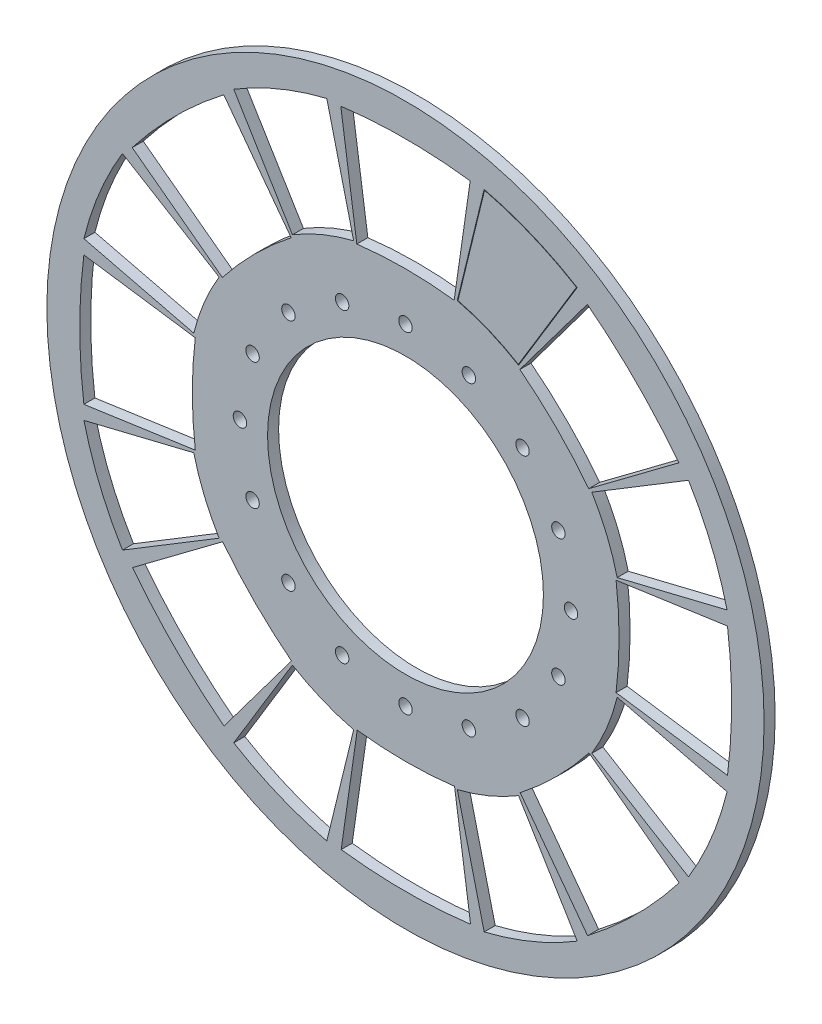
SolidWorks part; units mm, degrees
material "AISI 304"
ref_plane "Front Plane" through (0, 0, 0) normal (0, 0, 1) x (1, 0, 0)
ref_plane "Top Plane" through (0, 0, 0) normal (0, 1, 0) x (1, 0, 0)
ref_plane "Right Plane" through (0, 0, 0) normal (1, 0, 0) x (0, 0, -1)
sketch "Sketch1" plane through (0, 0, 0) normal (0, 0, 1) x (1, 0, 0)
  line L0 (0, 0) -> (0, 441.7053) construction
  line L3 (0, 0) -> (185.4371, 447.6848) construction
  line L4 (46.943, 191.8401) -> (71.3058, 291.4026)
  line L9 (226.8514, -146.4443) -> (147.5642, -85.5018) construction
  line L10 (85.3562, -147.7098) -> (146.2341, -227.0473) construction
  line L11 (56.8537, -258.9599) -> (43.882, -159.8025) construction
  line L12 (-44.0933, -159.8025) -> (-57.1463, -258.9498) construction
  line L13 (-146.4443, -226.8514) -> (-85.5018, -147.5642) construction
  line L14 (-147.7098, -85.3562) -> (-227.0473, -146.2341) construction
  line L18 (102.4577, 168.8451) -> (155.632, 256.4736)
  line L19 (191.8401, 46.943) -> (291.4026, 71.3058)
  line L20 (168.8451, 102.4577) -> (256.4736, 155.632)
  line L21 (168.8451, -102.4577) -> (256.4736, -155.632)
  line L22 (191.8401, -46.943) -> (291.4026, -71.3058)
  line L23 (46.943, -191.8401) -> (71.3058, -291.4026)
  line L24 (102.4577, -168.8451) -> (155.632, -256.4736)
  line L25 (-102.4577, -168.8451) -> (-155.632, -256.4736)
  line L26 (-46.943, -191.8401) -> (-71.3058, -291.4026)
  line L27 (-191.8401, -46.943) -> (-291.4026, -71.3058)
  line L28 (-168.8451, -102.4577) -> (-256.4736, -155.632)
  line L29 (-168.8451, 102.4577) -> (-256.4736, 155.632)
  line L30 (-191.8401, 46.943) -> (-291.4026, 71.3058)
  line L31 (-46.943, 191.8401) -> (-71.3058, 291.4026)
  line L32 (-102.4577, 168.8451) -> (-155.632, 256.4736)
  line L33 (0, 0) -> (-125, 0) construction
  line L34 (0, 125) -> (85.3562, 125) construction
  circle A1 centre (0, 0) radius 325
  circle A2 centre (0, 0) radius 125
  circle A5 centre (0, 0) radius 197.5 construction
  circle A6 centre (0, 0) radius 300 construction
  arc A11 (146.2341, -227.0473) -> (226.8514, -146.4443) centre (-136.1908, 136.0452) ccw construction
  arc A12 (85.3562, -147.7098) -> (147.5642, -85.5018) centre (-136.1908, 136.0452) ccw construction
  arc A13 (-57.1463, -258.9498) -> (56.8537, -258.9599) centre (-0.1056, 197.5) ccw construction
  arc A14 (-44.0933, -159.8025) -> (43.882, -159.8025) centre (-0.1056, 197.5) ccw construction
  arc A15 (-227.0473, -146.2341) -> (-146.4443, -226.8514) centre (136.0452, 136.1908) ccw construction
  arc A16 (-147.7098, -85.3562) -> (-85.5018, -147.5642) centre (136.0452, 136.1908) ccw construction
  arc A20 (46.943, 191.8401) -> (102.4577, 168.8451) centre (0, 0) cw
  arc A21 (71.3058, 291.4026) -> (155.632, 256.4736) centre (0, 0) cw
  arc A22 (256.4736, 155.632) -> (291.4026, 71.3058) centre (0, 0) cw
  arc A23 (168.8451, 102.4577) -> (191.8401, 46.943) centre (0, 0) cw
  arc A24 (291.4026, -71.3058) -> (256.4736, -155.632) centre (0, 0) cw
  arc A25 (191.8401, -46.943) -> (168.8451, -102.4577) centre (0, 0) cw
  arc A26 (155.632, -256.4736) -> (71.3058, -291.4026) centre (0, 0) cw
  arc A27 (102.4577, -168.8451) -> (46.943, -191.8401) centre (0, 0) cw
  arc A28 (-71.3058, -291.4026) -> (-155.632, -256.4736) centre (0, 0) cw
  arc A29 (-46.943, -191.8401) -> (-102.4577, -168.8451) centre (0, 0) cw
  arc A30 (-256.4736, -155.632) -> (-291.4026, -71.3058) centre (0, 0) cw
  arc A31 (-168.8451, -102.4577) -> (-191.8401, -46.943) centre (0, 0) cw
  arc A32 (-291.4026, 71.3058) -> (-256.4736, 155.632) centre (0, 0) cw
  arc A33 (-191.8401, 46.943) -> (-168.8451, 102.4577) centre (0, 0) cw
  arc A34 (-155.632, 256.4736) -> (-71.3058, 291.4026) centre (0, 0) cw
  arc A35 (-102.4577, 168.8451) -> (-46.943, 191.8401) centre (0, 0) cw
  circle A36 centre (0, 150) radius 6.1
  circle A37 centre (57.4025, 138.5819) radius 6.1
  circle A38 centre (106.066, 106.066) radius 6.1
  circle A39 centre (138.5819, 57.4025) radius 6.1
  circle A40 centre (150, 0) radius 6.1
  circle A41 centre (138.5819, -57.4025) radius 6.1
  circle A42 centre (106.066, -106.066) radius 6.1
  circle A43 centre (57.4025, -138.5819) radius 6.1
  circle A44 centre (0, -150) radius 6.1
  circle A45 centre (-57.4025, -138.5819) radius 6.1
  circle A46 centre (-106.066, -106.066) radius 6.1
  circle A47 centre (-138.5819, -57.4025) radius 6.1
  circle A48 centre (-150, 0) radius 6.1
  circle A49 centre (-138.5819, 57.4025) radius 6.1
  circle A50 centre (-106.066, 106.066) radius 6.1
  circle A51 centre (-57.4025, 138.5819) radius 6.1
  point P54 (0, 0)
  point P70 (0, 0)
  point P98 (0, 0)
  dimension "D1" = 250
  dimension "D2" = 650
  dimension "D5" = 395
  dimension "D3" = 600
  dimension "D6" = 17.5
  dimension "D7" = 8
  dimension "D8" = 12.2
  dimension "D4" = 22.5
  dimension "D9" = 150
  dimension "D10" = 16
extrude "Boss-Extrude1" add sketch "Sketch1" along normal blind 10
sketch "Sketch2" plane through (0, 0, 0) normal (0, 0, -1) x (-1, 0, 0)
  line L0 (-71.3058, 291.4026) -> (-46.943, 191.8401) construction
  line L1 (-102.4577, 168.8451) -> (-155.632, 256.4736) construction
  line L2 (-71.3058, 291.4026) -> (-46.943, 191.8401)
  line L3 (-102.4577, 168.8451) -> (-155.632, 256.4736)
  line L4 (-102.2893, 169.5314) -> (-154.9449, 256.3051)
  line L5 (-71.6725, 290.7977) -> (-47.5473, 192.2063)
  arc A0 (-46.943, 191.8401) -> (-102.4577, 168.8451) centre (0, 0) ccw construction
  arc A1 (-71.3058, 291.4026) -> (-155.632, 256.4736) centre (0, 0) ccw construction
  arc A2 (-46.943, 191.8401) -> (-102.4577, 168.8451) centre (0, 0) ccw
  arc A3 (-71.3058, 291.4026) -> (-155.632, 256.4736) centre (0, 0) ccw
  arc A4 (-47.5473, 192.2063) -> (-102.2893, 169.5314) centre (0, 0) ccw
  arc A5 (-71.6725, 290.7977) -> (-154.9449, 256.3051) centre (0, 0) ccw
  dimension "D1" = 0.5
extrude "Boss-Extrude2" add sketch "Sketch2" against normal blind 10 separate body contours A4 L4 A5 L5
sketch "Sketch3" plane through (0, 0, 0) normal (0, 0, -1) x (-1, 0, 0)
  line L0 (-57.5, 290.8396) -> (-43.25, 191.8401) construction
  line L1 (57.5, 290.8396) -> (43.25, 191.8401) construction
  line L2 (0, 194.4475) -> (0, 294.4475) construction
  line L3 (-46.943, 191.8401) -> (46.943, 191.8401) construction
  line L4 (71.3058, 291.4026) -> (-71.3058, 291.4026) construction
  line L5 (0, 291.4026) -> (0, 191.8401) construction
  line L6 (246.2079, 164.8906) -> (166.1284, 104.9636) construction
  line L7 (164.8906, 246.2079) -> (104.9636, 166.1284) construction
  line L8 (290.5852, -57.6054) -> (191.5856, -43.3554) construction
  line L9 (290.5852, 57.3946) -> (191.5856, 43.1446) construction
  line L10 (164.6362, -246.3133) -> (104.7092, -166.2338) construction
  line L11 (245.9535, -164.996) -> (165.8739, -105.069) construction
  line L12 (-57.8598, -290.6906) -> (-43.6098, -191.691) construction
  line L13 (57.1402, -290.6906) -> (42.8902, -191.691) construction
  line L14 (-246.5677, -164.7416) -> (-166.4882, -104.8146) construction
  line L15 (-165.2505, -246.0588) -> (-105.3235, -165.9793) construction
  line L16 (-290.945, 57.7544) -> (-191.9455, 43.5044) construction
  line L17 (-290.945, -57.2456) -> (-191.9455, -42.9956) construction
  line L18 (-164.996, 246.4623) -> (-105.069, 166.3828) construction
  line L19 (-246.3133, 165.1451) -> (-166.2338, 105.2181) construction
  line L20 (58.6346, 291.7034) -> (44.1003, 190.7285)
  line L21 (-58.6346, 291.7034) -> (-44.1003, 190.7285)
  line L22 (247.621, 164.6991) -> (165.9437, 103.5764)
  line L23 (164.6991, 247.621) -> (103.5764, 165.9437)
  line L24 (291.449, -58.74) -> (190.4741, -44.2057)
  line L25 (291.449, 58.5292) -> (190.4741, 43.9949)
  line L26 (164.4447, -247.7264) -> (103.322, -166.0491)
  line L27 (247.3666, -164.8045) -> (165.6892, -103.6818)
  line L28 (-58.9945, -291.5544) -> (-44.4602, -190.5795)
  line L29 (58.2748, -291.5544) -> (43.7405, -190.5795)
  line L30 (-247.9809, -164.5501) -> (-166.3035, -103.4274)
  line L31 (-165.059, -247.472) -> (-103.9362, -165.7946)
  line L32 (-291.8088, 58.8891) -> (-190.8339, 44.3548)
  line L33 (-291.8088, -58.3802) -> (-190.8339, -43.8459)
  line L34 (-164.8045, 247.8755) -> (-103.6818, 166.1981)
  line L35 (-247.7264, 164.9536) -> (-166.0491, 103.8309)
  arc A0 (-57.5, 290.8396) -> (57.5, 290.8396) centre (0, -165.5525) cw construction
  arc A1 (-43.25, 191.8401) -> (43.25, 191.8401) centre (0, -165.5525) cw construction
  arc A2 (104.9636, 166.1284) -> (166.1284, 104.9636) centre (-117.1687, -117.1687) cw construction
  arc A3 (164.8906, 246.2079) -> (246.2079, 164.8906) centre (-117.1687, -117.1687) cw construction
  arc A4 (191.5856, 43.1446) -> (191.5856, -43.3554) centre (-165.8069, -0.1054) cw construction
  arc A5 (290.5852, 57.3946) -> (290.5852, -57.6054) centre (-165.8069, -0.1054) cw construction
  arc A6 (165.8739, -105.069) -> (104.7092, -166.2338) centre (-117.4231, 117.0633) cw construction
  arc A7 (245.9535, -164.996) -> (164.6362, -246.3133) centre (-117.4231, 117.0633) cw construction
  arc A8 (42.8902, -191.691) -> (-43.6098, -191.691) centre (-0.3598, 165.7015) cw construction
  arc A9 (57.1402, -290.6906) -> (-57.8598, -290.6906) centre (-0.3598, 165.7015) cw construction
  arc A10 (-105.3235, -165.9793) -> (-166.4882, -104.8146) centre (116.8088, 117.3177) cw construction
  arc A11 (-165.2505, -246.0588) -> (-246.5677, -164.7416) centre (116.8088, 117.3177) cw construction
  arc A12 (-191.9455, -42.9956) -> (-191.9455, 43.5044) centre (165.4471, 0.2544) cw construction
  arc A13 (-290.945, -57.2456) -> (-290.945, 57.7544) centre (165.4471, 0.2544) cw construction
  arc A14 (-166.2338, 105.2181) -> (-105.069, 166.3828) centre (117.0633, -116.9142) cw construction
  arc A15 (-246.3133, 165.1451) -> (-164.996, 246.4623) centre (117.0633, -116.9142) cw construction
  arc A16 (-44.1003, 190.7285) -> (44.1003, 190.7285) centre (0, -165.5525) cw
  arc A17 (-58.6346, 291.7034) -> (58.6346, 291.7034) centre (0, -165.5525) cw
  arc A18 (103.5764, 165.9437) -> (165.9437, 103.5764) centre (-117.1687, -117.1687) cw
  arc A19 (164.6991, 247.621) -> (247.621, 164.6991) centre (-117.1687, -117.1687) cw
  arc A20 (190.4741, 43.9949) -> (190.4741, -44.2057) centre (-165.8069, -0.1054) cw
  arc A21 (291.449, 58.5292) -> (291.449, -58.74) centre (-165.8069, -0.1054) cw
  arc A22 (165.6892, -103.6818) -> (103.322, -166.0491) centre (-117.4231, 117.0633) cw
  arc A23 (247.3666, -164.8045) -> (164.4447, -247.7264) centre (-117.4231, 117.0633) cw
  arc A24 (43.7405, -190.5795) -> (-44.4602, -190.5795) centre (-0.3598, 165.7015) cw
  arc A25 (58.2748, -291.5544) -> (-58.9945, -291.5544) centre (-0.3598, 165.7015) cw
  arc A26 (-103.9362, -165.7946) -> (-166.3035, -103.4274) centre (116.8088, 117.3177) cw
  arc A27 (-165.059, -247.472) -> (-247.9809, -164.5501) centre (116.8088, 117.3177) cw
  arc A28 (-190.8339, -43.8459) -> (-190.8339, 44.3548) centre (165.4471, 0.2544) cw
  arc A29 (-291.8088, -58.3802) -> (-291.8088, 58.8891) centre (165.4471, 0.2544) cw
  arc A30 (-166.0491, 103.8309) -> (-103.6818, 166.1981) centre (117.0633, -116.9142) cw
  arc A31 (-247.7264, 164.9536) -> (-164.8045, 247.8755) centre (117.0633, -116.9142) cw
  point P55 (-0.1799, 0.0745)
  point P104 (-0.1799, 0.0745)
  dimension "D1" = 360
  dimension "D2" = 460
  dimension "D3" = 86.5
  dimension "D4" = 115
  dimension "D5" = 8
  dimension "D6" = 1
  dimension "D7" = 8
extrude "Cut-Extrude1" cut sketch "Sketch3" against normal blind 10
